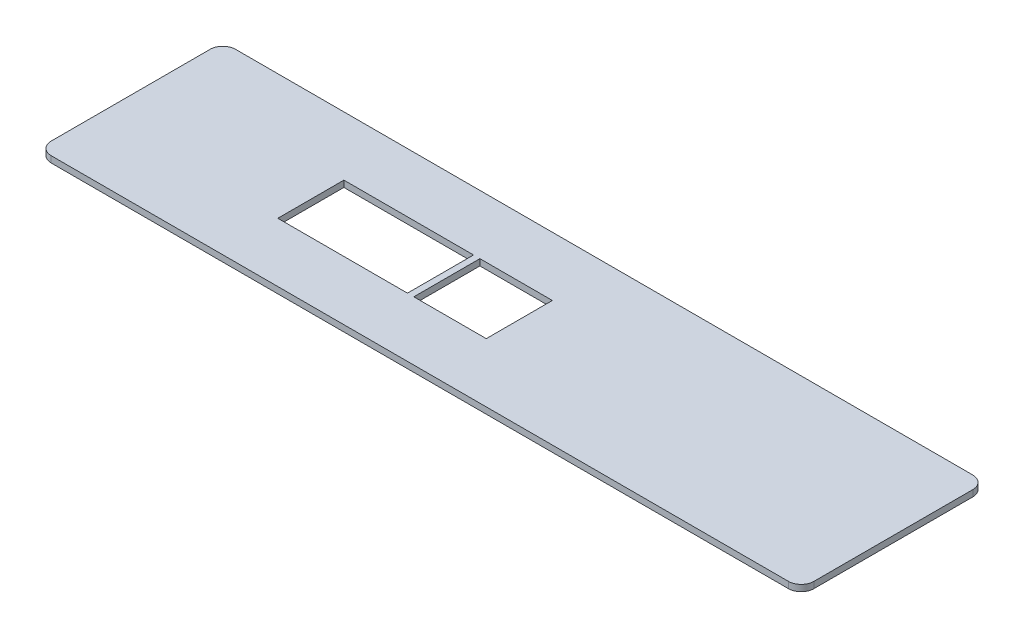
SolidWorks part; units mm, degrees
ref_plane "Front Plane" through (0, 0, 0) normal (0, 0, 1) x (1, 0, 0)
ref_plane "Top Plane" through (0, 0, 0) normal (0, 1, 0) x (1, 0, 0)
ref_plane "Right Plane" through (0, 0, 0) normal (1, 0, 0) x (0, 0, -1)
sketch "Sketch1" plane through (0, 0, 0) normal (0, 1, 0) x (1, 0, 0)
  line L1 (0, 14.5) -> (120, 14.5)
  line L2 (0, 14.5) -> (0, -14.5)
  line L3 (0, -14.5) -> (120, -14.5)
  line L4 (120, 14.5) -> (120, -14.5)
  line L5 (28.75, 5) -> (48.75, 5)
  line L6 (28.75, 5) -> (28.75, -5)
  line L7 (28.75, -5) -> (48.75, -5)
  line L8 (48.75, 5) -> (48.75, -5)
  line L9 (49.75, 5) -> (60.75, 5)
  line L10 (49.75, 5) -> (49.75, -5)
  line L11 (49.75, -5) -> (60.75, -5)
  line L12 (60.75, 5) -> (60.75, -5)
  point P4 (0, 0)
  point P10 (28.75, 0)
  point P15 (49.75, 0)
  dimension "D1" = 29
  dimension "D2" = 120
  dimension "D3" = 28.75
  dimension "D4" = 20
  dimension "D5" = 10
  dimension "D6" = 11
  dimension "D7" = 10
  dimension "D8" = 1
sketch "Sketch2" plane through (0, 0, 0) normal (0, 1, 0) x (1, 0, 0)
  line L0 (0, 12.5) -> (0, -12.5)
  line L1 (2, -14.5) -> (118, -14.5)
  line L2 (120, -12.5) -> (120, 12.5)
  line L3 (118, 14.5) -> (2, 14.5)
  line L4 (48.75, 5) -> (48.75, -5) construction
  line L5 (28.35, 5.2) -> (48.75, 5.2)
  line L6 (28.35, 5.2) -> (28.35, -5.2)
  line L7 (28.35, -5.2) -> (48.75, -5.2)
  line L8 (48.75, 5.2) -> (48.75, -5.2)
  line L9 (28.75, 5) -> (28.75, -5) construction
  line L10 (28.75, 5) -> (48.75, 5) construction
  line L11 (28.75, -5) -> (48.75, -5) construction
  line L12 (49.75, 5) -> (49.75, -5) construction
  line L13 (49.75, 5.2) -> (61.15, 5.2)
  line L14 (49.75, 5.2) -> (49.75, -5.2)
  line L15 (49.75, -5.2) -> (61.15, -5.2)
  line L16 (61.15, 5.2) -> (61.15, -5.2)
  line L17 (49.75, 5) -> (60.75, 5) construction
  line L18 (49.75, -5) -> (60.75, -5) construction
  line L19 (60.75, 5) -> (60.75, -5) construction
  arc A0 (118, 14.5) -> (120, 12.5) centre (118, 12.5) cw
  arc A1 (120, -12.5) -> (118, -14.5) centre (118, -12.5) cw
  arc A2 (2, -14.5) -> (0, -12.5) centre (2, -12.5) cw
  arc A3 (2, 14.5) -> (0, 12.5) centre (2, 12.5) ccw
  point P10 (120, 14.5)
  point P13 (120, -14.5)
  point P16 (0, -14.5)
  point P19 (0, 14.5)
  dimension "D1" = 2
  dimension "D2" = 0.4
  dimension "D3" = 0.2
  dimension "D4" = 0.2
  dimension "D5" = 0.2
  dimension "D6" = 0.2
  dimension "D7" = 0.4
extrude "Boss-Extrude1" add sketch "Sketch2" along normal blind 1
